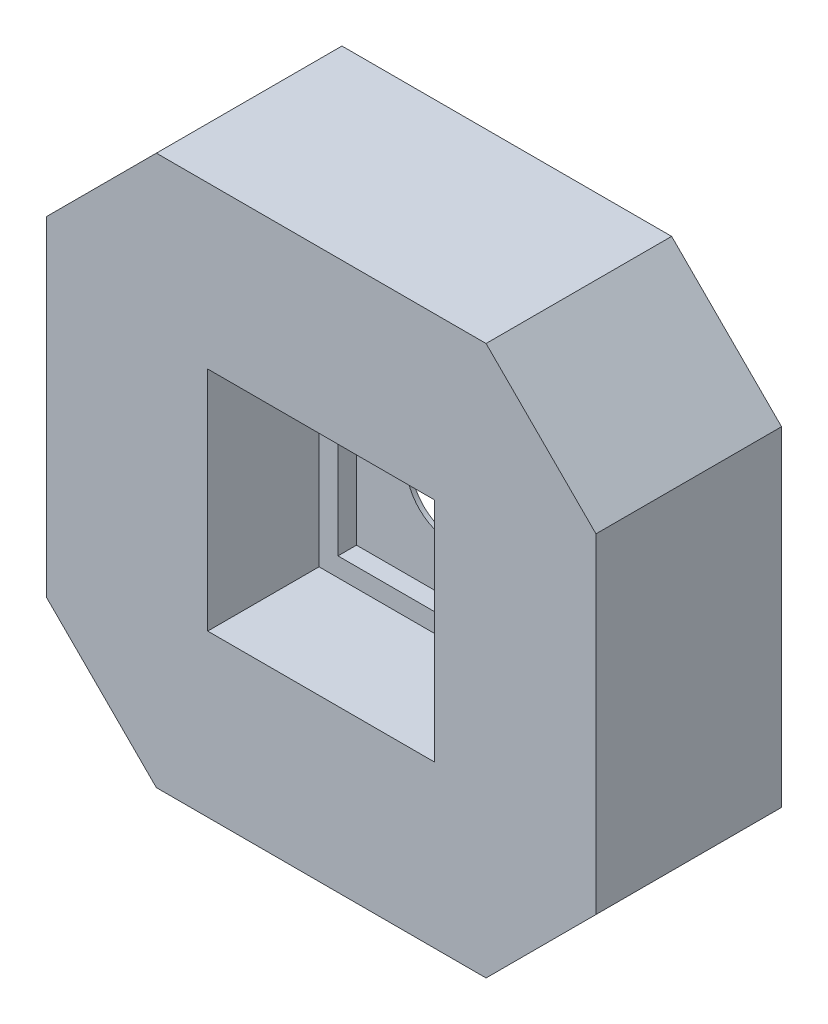
SolidWorks part; units mm, degrees
ref_plane "前视基准面" through (0, 0, 0) normal (0, 0, 1) x (1, 0, 0)
ref_plane "上视基准面" through (0, 0, 0) normal (0, 1, 0) x (1, 0, 0)
ref_plane "右视基准面" through (0, 0, 0) normal (1, 0, 0) x (0, 0, -1)
sketch "草图1" plane through (0, 0, 0) normal (0, 0, 1) x (1, 0, 0)
  line L0 (-305, 183) -> (-183, 305)
  line L1 (-183, 305) -> (183, 305)
  line L2 (-305, 183) -> (-305, -183)
  line L3 (-183, -305) -> (183, -305)
  line L4 (305, 183) -> (305, -183)
  line L5 (-305, 305) -> (305, -305) construction
  line L6 (-305, -305) -> (305, 305) construction
  line L7 (-305, -183) -> (-183, -305)
  line L8 (183, -305) -> (305, -183)
  line L9 (183, 305) -> (305, 183)
  point P0 (0, 0)
  dimension "D1" = 610
  dimension "D2" = 610
extrude "凸台-拉伸1" add sketch "草图1" along normal blind 206
sketch "草图2" plane through (0, 0, 206) normal (0, 0, 1) x (1, 0, 0)
  line L1 (-126, 126) -> (126, 126)
  line L2 (-126, 126) -> (-126, -126)
  line L3 (-126, -126) -> (126, -126)
  line L4 (126, 126) -> (126, -126)
  line L5 (-126, 126) -> (126, -126) construction
  line L6 (-126, -126) -> (126, 126) construction
  point P0 (0, 0)
  dimension "D1" = 252
  dimension "D2" = 252
extrude "切除-拉伸1" cut sketch "草图2" against normal blind 123.6
sketch "草图3" plane through (0, 0, 206) normal (0, 0, 1) x (1, 0, 0)
  line L1 (-105, 105) -> (105, 105)
  line L2 (-105, 105) -> (-105, -105)
  line L3 (-105, -105) -> (105, -105)
  line L4 (105, 105) -> (105, -105)
  line L5 (-105, 105) -> (105, -105) construction
  line L6 (-105, -105) -> (105, 105) construction
  point P0 (0, 0)
  dimension "D1" = 210
  dimension "D2" = 210
extrude "切除-拉伸2" cut sketch "草图3" against normal blind 144.2
shell "抽壳1" thickness 5
sketch "草图4" plane through (0, 0, 61.8) normal (0, 0, 1) x (1, 0, 0)
  circle A0 centre (0, 0) radius 50
  dimension "D1" = 100
extrude "切除-拉伸3" cut sketch "草图4" against normal through all
ref_plane "基准面1" through (0, 91.5, 0) normal (0, 1, 0) x (1, 0, 0)
sketch "草图5" plane through (0, 91.5, 0) normal (0, 1, 0) x (1, 0, 0)
  line L0 (-131, -82.4) -> (-300, -112.1993)
  line L1 (-131, -77.4) -> (-131, -201) construction
  line L2 (-300, -201) -> (-300, 0) construction
  line L3 (-131, -77.4) -> (131, -77.4) construction
  line L4 (-300, -112.1993) -> (-300, -200.8648)
  line L5 (-300, -200.8648) -> (-131, -200.8648)
  line L6 (-131, -200.8648) -> (-131, -82.4)
  dimension "D1" = 80
  dimension "D2" = 5
extrude "凸台-拉伸2" add sketch "草图5" against normal blind 10
mirror "镜向1" about plane through (0, 0, 0) normal (0, 1, 0) of "凸台-拉伸2"
pattern_circular "阵列(圆周)1" count 4 over 360 about axis through (0, 0, 0) along (0, 0, 1) of "镜向1", "凸台-拉伸2"
